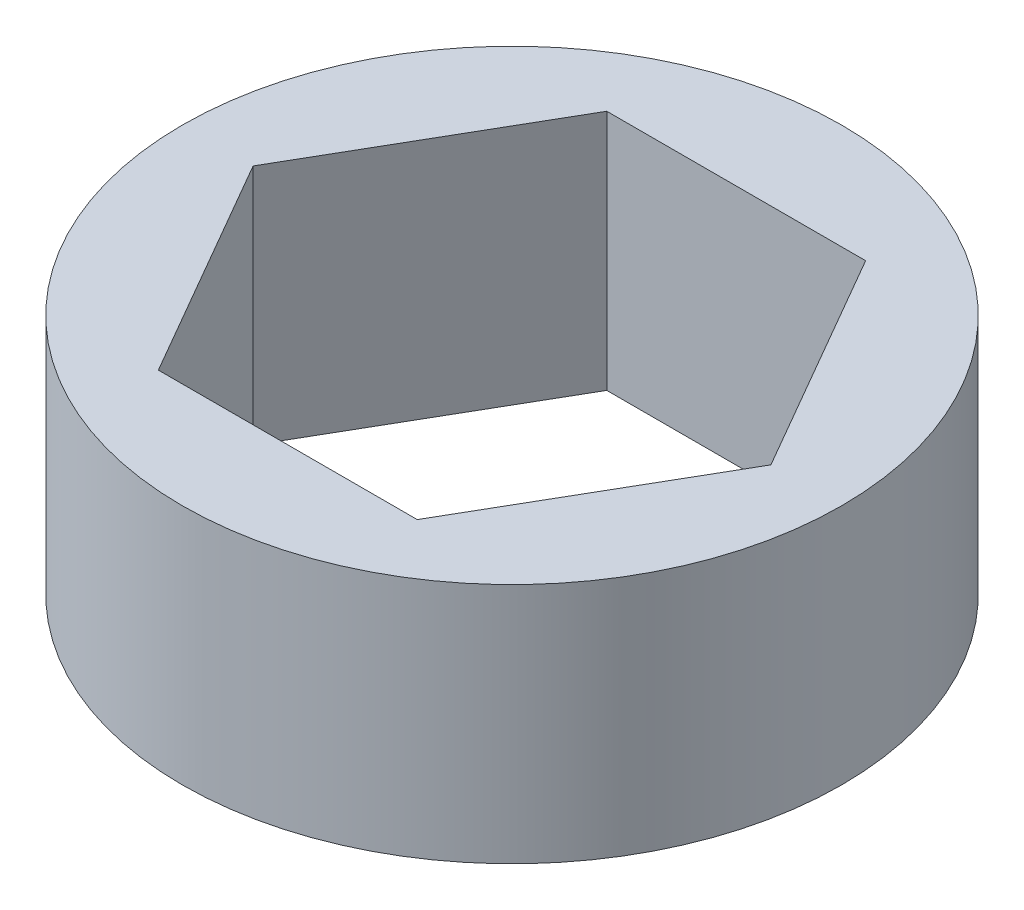
SolidWorks part; units mm, degrees
ref_plane "Front Plane" through (0, 0, 0) normal (0, 0, 1) x (1, 0, 0)
ref_plane "Top Plane" through (0, 0, 0) normal (0, 1, 0) x (1, 0, 0)
ref_plane "Right Plane" through (0, 0, 0) normal (1, 0, 0) x (0, 0, -1)
sketch "Sketch1" plane through (0, 0, 0) normal (0, 1, 0) x (1, 0, 0)
  line L1 (7.479, 0) -> (3.7395, 6.477)
  line L2 (3.7395, 6.477) -> (-3.7395, 6.477)
  line L3 (-3.7395, 6.477) -> (-7.479, 0)
  line L4 (-7.479, 0) -> (-3.7395, -6.477)
  line L5 (-3.7395, -6.477) -> (3.7395, -6.477)
  line L6 (3.7395, -6.477) -> (7.479, 0)
  circle A0 centre (0, 0) radius 6.477 construction
  circle A1 centre (0, 0) radius 9.525
  dimension "D2" = 19.05
  dimension "D1" = 12.954
extrude "Boss-Extrude1" add sketch "Sketch1" along normal blind 63.5
sketch "Sketch2" [suppressed] plane through (0, 63.5, 0) normal (0, 1, 0) x (1, 0, 0)
  circle A0 centre (0, 0) radius 9.525
  circle A1 centre (0, 0) radius 9.525 construction
extrude "Cut-Extrude1" [suppressed] cut sketch "Sketch2" against normal offset from surface (60.325 mm away) 3.175
sketch "Sketch3" plane through (0, 63.5, 0) normal (0, 1, 0) x (1, 0, 0)
  circle A0 centre (0, 0) radius 9.525
  circle A1 centre (0, 0) radius 9.525 construction
extrude "Cut-Extrude2" cut sketch "Sketch3" against normal offset from surface (56.515 mm away) 6.985 up to face at (0, 0, 9.525)
